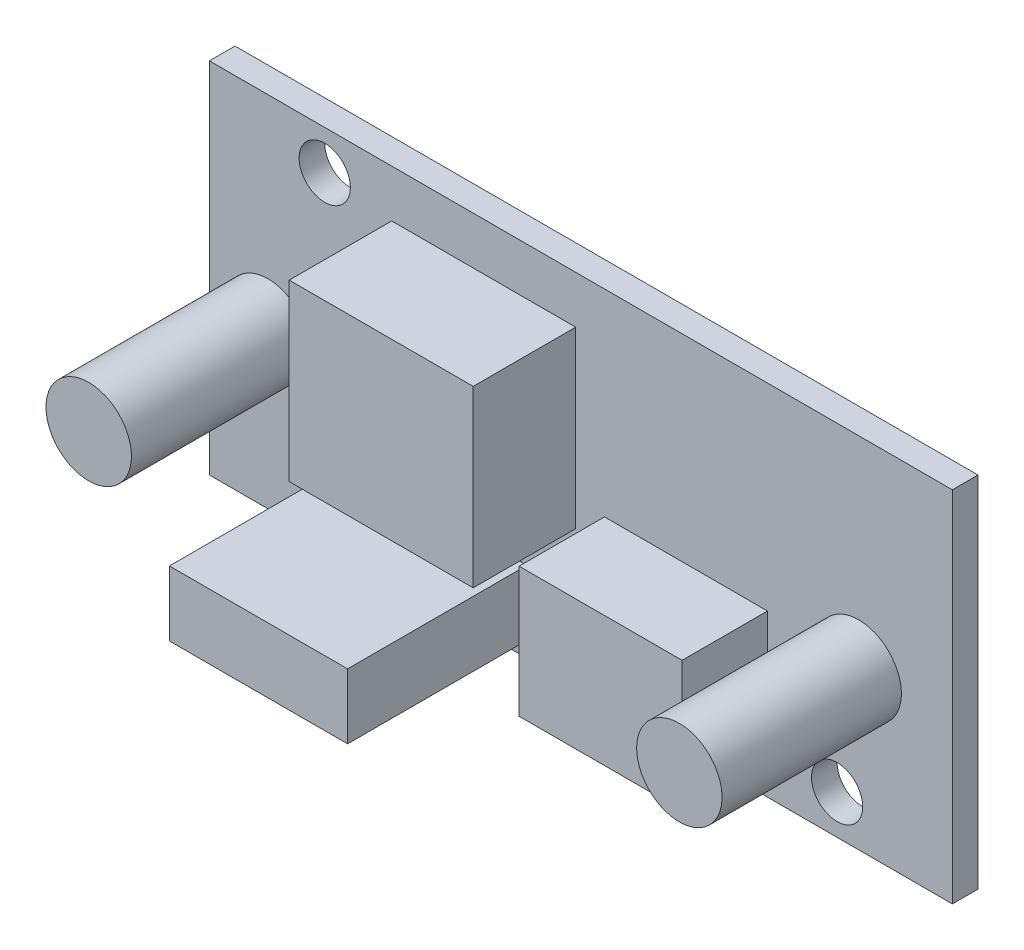
SolidWorks part; units mm, degrees
ref_plane "Front Plane" through (0, 0, 0) normal (0, 0, 1) x (1, 0, 0)
ref_plane "Top Plane" through (0, 0, 0) normal (0, 1, 0) x (1, 0, 0)
ref_plane "Right Plane" through (0, 0, 0) normal (1, 0, 0) x (0, 0, -1)
sketch "Sketch1" plane through (0, 0, 0) normal (0, 0, 1) x (1, 0, 0)
  line L1 (0, 0) -> (43.5, 0)
  line L2 (0, 0) -> (0, 21)
  line L3 (0, 21) -> (43.5, 21)
  line L4 (43.5, 0) -> (43.5, 21)
  circle A0 centre (6.75, 18.7) radius 1.5
  circle A1 centre (36.75, 2.3) radius 1.5
  dimension "D3" = 30
  dimension "D1" = 43.5
  dimension "D2" = 21
  dimension "D4" = 2.3
  dimension "D5" = 2.3
  dimension "D6" = 6.75
  dimension "D7" = 6.75
extrude "Boss-Extrude1" add sketch "Sketch1" along normal blind 1.5
sketch "Sketch2" plane through (0, 0, 1.5) normal (0, 0, 1) x (1, 0, 0)
  line L1 (8.1561, 0.9106) -> (18.5893, 0.9106)
  line L2 (8.1561, 0.9106) -> (8.1561, 4.7157)
  line L3 (8.1561, 4.7157) -> (18.5893, 4.7157)
  line L4 (18.5893, 0.9106) -> (18.5893, 4.7157)
  circle A0 centre (3.4305, 9.1652) radius 2.5
  circle A1 centre (38.0136, 9.1652) radius 2.5
extrude "Boss-Extrude2" add sketch "Sketch2" along normal blind 10.5
sketch "Sketch3" plane through (0, 0, 1.5) normal (0, 0, 1) x (1, 0, 0)
  line L1 (10.6723, 18.2175) -> (21.4431, 18.2175)
  line L2 (10.6723, 18.2175) -> (10.6723, 7.9991)
  line L3 (10.6723, 7.9991) -> (21.4431, 7.9991)
  line L4 (21.4431, 18.2175) -> (21.4431, 7.9991)
extrude "Boss-Extrude3" add sketch "Sketch3" along normal blind 6
sketch "Sketch4" plane through (0, 0, 1.5) normal (0, 0, 1) x (1, 0, 0)
  line L1 (23.1309, 9.4413) -> (32.6742, 9.4413)
  line L2 (23.1309, 9.4413) -> (23.1309, 1.8312)
  line L3 (23.1309, 1.8312) -> (32.6742, 1.8312)
  line L4 (32.6742, 9.4413) -> (32.6742, 1.8312)
extrude "Boss-Extrude4" add sketch "Sketch4" along normal blind 5
